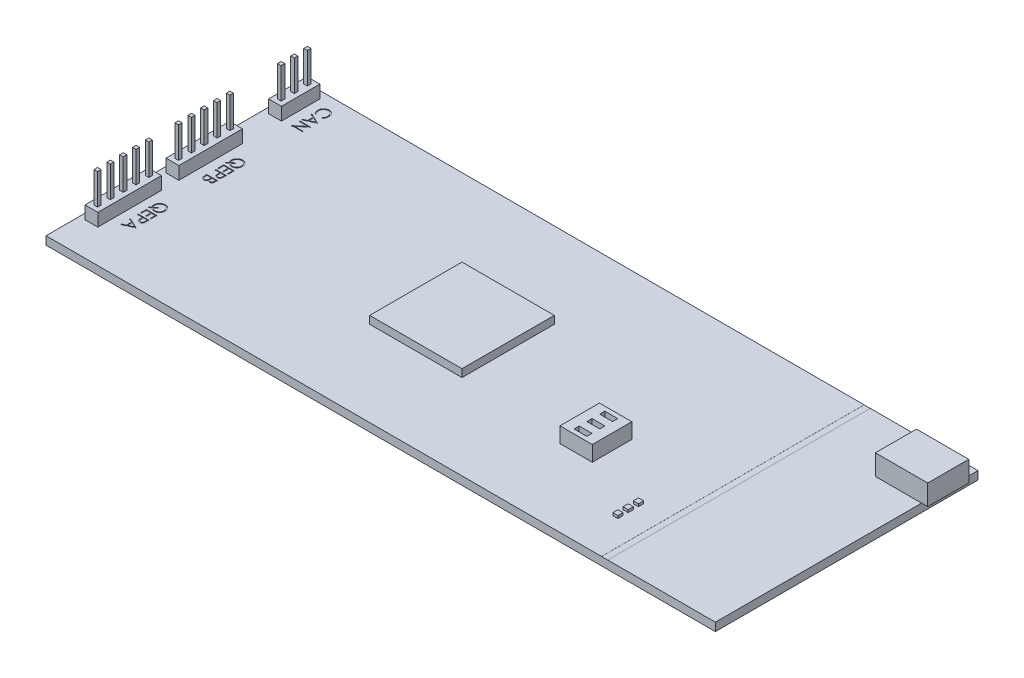
SolidWorks part; units mm, degrees
ref_plane "Ebene vorne" through (0, 0, 0) normal (0, 0, 1) x (1, 0, 0)
ref_plane "Ebene oben" through (0, 0, 0) normal (0, 1, 0) x (1, 0, 0)
ref_plane "Ebene rechts" through (0, 0, 0) normal (1, 0, 0) x (0, 0, -1)
sketch "Skizze1" plane through (0, 0, 0) normal (0, 1, 0) x (1, 0, 0)
  line L1 (-65.25, -25.6) -> (65.25, -25.6)
  line L2 (-65.25, -25.6) -> (-65.25, 25.6)
  line L3 (-65.25, 25.6) -> (65.25, 25.6)
  line L4 (65.25, -25.6) -> (65.25, 25.6)
  line L5 (-65.25, -25.6) -> (65.25, 25.6) construction
  line L6 (-65.25, 25.6) -> (65.25, -25.6) construction
  point P0 (0, 0)
  dimension "D1" = 51.2
  dimension "D2" = 130.5
extrude "Aufsatz-Linear austragen1" add sketch "Skizze1" along normal blind 1.6
sketch "Skizze2" plane through (65.25, 0, 0) normal (1, 0, 0) x (0, 0, -1)
  line L0 (-25.6, 1.6) -> (25.6, 1.6) construction
  line L1 (14.6, 1.6) -> (22.6, 1.6)
  line L2 (14.6, 1.6) -> (14.6, 5.6)
  line L3 (14.6, 5.6) -> (22.6, 5.6)
  line L4 (22.6, 1.6) -> (22.6, 5.6)
  line L5 (25.6, 1.6) -> (25.6, 0) construction
  dimension "D1" = 8
  dimension "D2" = 4
  dimension "D3" = 3
extrude "Aufsatz-Linear austragen2" add sketch "Skizze2" along normal blind 1.2 and the other way blind 9
sketch "Skizze4" plane through (0, 1.6, 0) normal (0, 1, 0) x (1, 0, 0)
  line L0 (65.25, 25.6) -> (-65.25, 25.6) construction
  line L1 (-64.15, 24.2) -> (-61.65, 24.2)
  line L2 (-64.15, 24.2) -> (-64.15, 16.7)
  line L3 (-64.15, 16.7) -> (-61.65, 16.7)
  line L4 (-61.65, 24.2) -> (-61.65, 16.7)
  line L5 (-64.15, 9.1) -> (-61.65, 9.1)
  line L6 (-64.15, 9.1) -> (-64.15, -3.3)
  line L7 (-64.15, -3.3) -> (-61.65, -3.3)
  line L8 (-61.65, 9.1) -> (-61.65, -3.3)
  line L9 (-64.15, -6.7) -> (-61.65, -6.7)
  line L10 (-64.15, -6.7) -> (-64.15, -19.1)
  line L11 (-64.15, -19.1) -> (-61.65, -19.1)
  line L12 (-61.65, -6.7) -> (-61.65, -19.1)
  line L13 (-65.25, 25.6) -> (-65.25, -25.6) construction
  dimension "D1" = 2.5
  dimension "D2" = 7.5
  dimension "D3" = 1.4
  dimension "D4" = 1.1
  dimension "D5" = 16.5
  dimension "D6" = 32.3
  dimension "D7" = 12.4
extrude "Aufsatz-Linear austragen3" add sketch "Skizze4" along normal blind 2.5
sketch "Skizze5" plane through (0, 4.1, 0) normal (0, 1, 0) x (1, 0, 0)
  line L0 (-62.9, 29.2916) -> (-62.9, -22.1565) construction
  line L1 (-64.15, 24.2) -> (-64.15, 16.7) construction
  line L2 (-61.65, 16.7) -> (-61.65, 24.2) construction
  line L3 (-66.6105, 20.45) -> (-60.666, 20.45) construction
  line L4 (-63.25, 23.35) -> (-62.55, 23.35)
  line L5 (-63.25, 23.35) -> (-63.25, 22.65)
  line L6 (-63.25, 22.65) -> (-62.55, 22.65)
  line L7 (-62.55, 23.35) -> (-62.55, 22.65)
  line L8 (-63.25, 20.8) -> (-62.55, 20.8)
  line L9 (-63.25, 20.8) -> (-63.25, 20.1)
  line L10 (-63.25, 20.1) -> (-62.55, 20.1)
  line L11 (-62.55, 20.8) -> (-62.55, 20.1)
  line L12 (-63.25, 18.25) -> (-62.55, 18.25)
  line L13 (-63.25, 18.25) -> (-63.25, 17.55)
  line L14 (-63.25, 17.55) -> (-62.55, 17.55)
  line L15 (-62.55, 18.25) -> (-62.55, 17.55)
  line L16 (-61.65, 24.2) -> (-64.15, 24.2) construction
  line L17 (-64.15, 16.7) -> (-61.65, 16.7) construction
  line L18 (-68.1087, 2.9) -> (-59.7938, 2.9) construction
  line L19 (-63.25, 8.25) -> (-62.55, 8.25)
  line L20 (-63.25, 8.25) -> (-63.25, 7.55)
  line L21 (-63.25, 7.55) -> (-62.55, 7.55)
  line L22 (-62.55, 8.25) -> (-62.55, 7.55)
  line L23 (-63.25, 5.75) -> (-62.55, 5.75)
  line L24 (-63.25, 5.75) -> (-63.25, 5.05)
  line L25 (-63.25, 5.05) -> (-62.55, 5.05)
  line L26 (-62.55, 5.75) -> (-62.55, 5.05)
  line L27 (-63.25, 3.25) -> (-62.55, 3.25)
  line L28 (-63.25, 3.25) -> (-63.25, 2.55)
  line L29 (-63.25, 2.55) -> (-62.55, 2.55)
  line L30 (-62.55, 3.25) -> (-62.55, 2.55)
  line L31 (-63.25, 0.75) -> (-62.55, 0.75)
  line L32 (-63.25, 0.75) -> (-63.25, 0.05)
  line L33 (-63.25, 0.05) -> (-62.55, 0.05)
  line L34 (-62.55, 0.75) -> (-62.55, 0.05)
  line L35 (-63.25, -1.75) -> (-62.55, -1.75)
  line L36 (-63.25, -1.75) -> (-63.25, -2.45)
  line L37 (-63.25, -2.45) -> (-62.55, -2.45)
  line L38 (-62.55, -1.75) -> (-62.55, -2.45)
  line L39 (-63.25, -7.55) -> (-62.55, -7.55)
  line L40 (-63.25, -7.55) -> (-63.25, -8.25)
  line L41 (-63.25, -8.25) -> (-62.55, -8.25)
  line L42 (-62.55, -7.55) -> (-62.55, -8.25)
  line L43 (-63.25, -10.05) -> (-62.55, -10.05)
  line L44 (-63.25, -10.05) -> (-63.25, -10.75)
  line L45 (-63.25, -10.75) -> (-62.55, -10.75)
  line L46 (-62.55, -10.05) -> (-62.55, -10.75)
  line L47 (-63.25, -12.55) -> (-62.55, -12.55)
  line L48 (-63.25, -12.55) -> (-63.25, -13.25)
  line L49 (-63.25, -13.25) -> (-62.55, -13.25)
  line L50 (-62.55, -12.55) -> (-62.55, -13.25)
  line L51 (-63.25, -15.05) -> (-62.55, -15.05)
  line L52 (-63.25, -15.05) -> (-63.25, -15.75)
  line L53 (-63.25, -15.75) -> (-62.55, -15.75)
  line L54 (-62.55, -15.05) -> (-62.55, -15.75)
  line L55 (-63.25, -17.55) -> (-62.55, -17.55)
  line L56 (-63.25, -17.55) -> (-63.25, -18.25)
  line L57 (-63.25, -18.25) -> (-62.55, -18.25)
  line L58 (-62.55, -17.55) -> (-62.55, -18.25)
  line L59 (-61.65, 9.1) -> (-64.15, 9.1) construction
  line L60 (-64.15, -3.3) -> (-61.65, -3.3) construction
  line L61 (-67.6279, -12.9) -> (-60.666, -12.9) construction
  line L62 (-61.65, -6.7) -> (-64.15, -6.7) construction
  line L63 (-64.15, -19.1) -> (-61.65, -19.1) construction
  dimension "D1" = 0.7
  dimension "D2" = 4.4
  dimension "D3" = 5.7
  dimension "D4" = 10.7
  dimension "D5" = 5.7
  dimension "D6" = 10.7
extrude "Aufsatz-Linear austragen4" add sketch "Skizze5" along normal blind 6
sketch "Skizze6" plane through (0, 1.6, 0) normal (0, 1, 0) x (1, 0, 0)
  line L0 (65.25, 25.6) -> (-65.25, 25.6) construction
  line L1 (43.05, 25.6) -> (44.25, 25.6)
  line L2 (43.05, 25.6) -> (43.05, -25.6)
  line L3 (43.05, -25.6) -> (44.25, -25.6)
  line L4 (44.25, 25.6) -> (44.25, -25.6)
  line L5 (-65.25, -25.6) -> (65.25, -25.6) construction
  line L6 (65.25, -25.6) -> (65.25, 14.6) construction
  dimension "D1" = 1.2
  dimension "D2" = 21
extrude "Schnitt-Linear austragen1" cut sketch "Skizze6" against normal blind 0.01
sketch "Skizze7" plane through (0, 1.6, 0) normal (0, 1, 0) x (1, 0, 0)
  line L0 (-73.4444, 0) -> (19.4459, 0) construction
  line L1 (-18.75, -9) -> (-0.75, -9)
  line L2 (-18.75, -9) -> (-18.75, 9)
  line L3 (-18.75, 9) -> (-0.75, 9)
  line L4 (-0.75, -9) -> (-0.75, 9)
  line L5 (-18.75, -9) -> (-0.75, 9) construction
  line L6 (-18.75, 9) -> (-0.75, -9) construction
  line L7 (65.25, -25.6) -> (65.25, 14.6) construction
  point P0 (-9.75, 0)
  dimension "D1" = 18
  dimension "D2" = 66
extrude "Aufsatz-Linear austragen5" add sketch "Skizze7" along normal blind 1.5
sketch "Skizze8" plane through (0, 1.6, 0) normal (0, 1, 0) x (1, 0, 0)
  line L0 (65.25, -25.6) -> (65.25, 14.6) construction
  line L1 (19.95, -2.9) -> (26.25, -2.9)
  line L2 (19.95, -2.9) -> (19.95, -10.6)
  line L3 (19.95, -10.6) -> (26.25, -10.6)
  line L4 (26.25, -2.9) -> (26.25, -10.6)
  line L5 (19.95, -2.9) -> (26.25, -10.6) construction
  line L6 (19.95, -10.6) -> (26.25, -2.9) construction
  line L7 (-65.25, -25.6) -> (43.05, -25.6) construction
  point P0 (23.1, -6.75)
  dimension "D1" = 7.7
  dimension "D2" = 6.3
  dimension "D3" = 39
  dimension "D4" = 15
extrude "Aufsatz-Linear austragen6" add sketch "Skizze8" along normal blind 3
sketch "Skizze9" plane through (0, 4.6, 0) normal (0, 1, 0) x (1, 0, 0)
  line L0 (17.552, -6.75) -> (26.77, -6.75) construction
  line L1 (21.85, -3.75) -> (24.35, -3.75)
  line L2 (21.85, -3.75) -> (21.85, -4.75)
  line L3 (21.85, -4.75) -> (24.35, -4.75)
  line L4 (24.35, -3.75) -> (24.35, -4.75)
  line L5 (21.85, -6.25) -> (24.35, -6.25)
  line L6 (21.85, -6.25) -> (21.85, -7.25)
  line L7 (21.85, -7.25) -> (24.35, -7.25)
  line L8 (24.35, -6.25) -> (24.35, -7.25)
  line L9 (21.85, -8.75) -> (24.35, -8.75)
  line L10 (21.85, -8.75) -> (21.85, -9.75)
  line L11 (21.85, -9.75) -> (24.35, -9.75)
  line L12 (24.35, -8.75) -> (24.35, -9.75)
  line L13 (26.25, -2.9) -> (19.95, -2.9) construction
  line L14 (19.95, -10.6) -> (26.25, -10.6) construction
  line L15 (23.1, -1.7044) -> (23.1, -10.9665) construction
  line L16 (19.95, -2.9) -> (19.95, -10.6) construction
  line L17 (26.25, -10.6) -> (26.25, -2.9) construction
  dimension "D1" = 2.5
  dimension "D2" = 1
  dimension "D3" = 4
extrude "Schnitt-Linear austragen2" cut sketch "Skizze9" against normal blind 1
sketch "Skizze10" plane through (0, 1.6, 0) normal (0, 1, 0) x (1, 0, 0)
  line L0 (21.5527, -15.1) -> (30.3375, -15.1) construction
  line L1 (37.25, -12.6) -> (38.25, -12.6)
  line L2 (37.25, -12.6) -> (37.25, -13.6)
  line L3 (37.25, -13.6) -> (38.25, -13.6)
  line L4 (38.25, -12.6) -> (38.25, -13.6)
  line L5 (37.25, -14.6) -> (38.25, -14.6)
  line L6 (37.25, -14.6) -> (37.25, -15.6)
  line L7 (37.25, -15.6) -> (38.25, -15.6)
  line L8 (38.25, -14.6) -> (38.25, -15.6)
  line L9 (37.25, -16.6) -> (38.25, -16.6)
  line L10 (37.25, -16.6) -> (37.25, -17.6)
  line L11 (37.25, -17.6) -> (38.25, -17.6)
  line L12 (38.25, -16.6) -> (38.25, -17.6)
  line L13 (65.25, -25.6) -> (65.25, 14.6) construction
  line L14 (-65.25, -25.6) -> (43.05, -25.6) construction
  dimension "D1" = 1
  dimension "D2" = 5
  dimension "D3" = 27
  dimension "D4" = 8
extrude "Aufsatz-Linear austragen7" add sketch "Skizze10" along normal blind 0.5
sketch "Skizze11" plane through (0, 1.6, 0) normal (0, 1, 0) x (1, 0, 0)
  line L0 (-59.8881, 7.426) -> (-59.8881, -1.9268) construction
  line L1 (-59.8881, -8.3532) -> (-59.8881, -16.8393) construction
  line L2 (-59.8881, 23.3599) -> (-59.8881, 16.8894) construction
  text T0 "QEPB" font "Century Gothic" height in points 8
  text T1 "QEPA" font "Century Gothic" height in points 8
  text T2 "CAN" font "Century Gothic" height 2.1167
extrude "Schnitt-Linear austragen3" cut sketch "Skizze11" against normal blind 0.1
